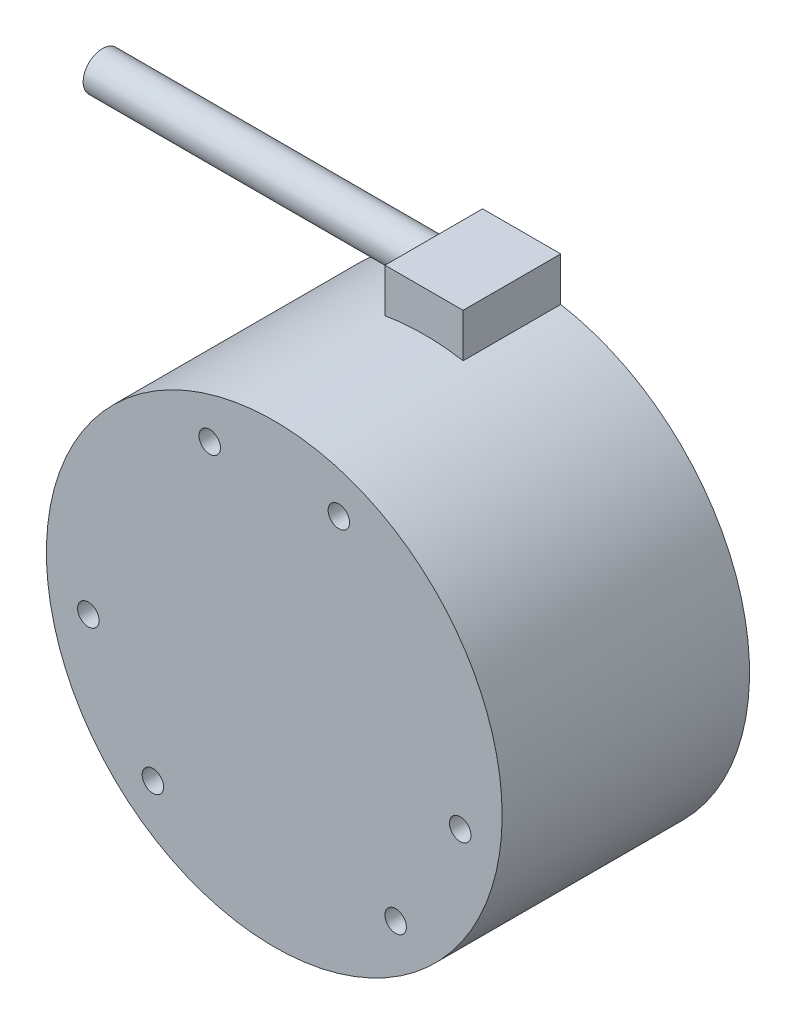
SolidWorks part; units mm, degrees
ref_plane "前视基准面" through (0, 0, 0) normal (0, 0, 1) x (1, 0, 0)
ref_plane "上视基准面" through (0, 0, 0) normal (0, 1, 0) x (1, 0, 0)
ref_plane "右视基准面" through (0, 0, 0) normal (1, 0, 0) x (0, 0, -1)
sketch "草图1" plane through (0, 0, 0) normal (0, 0, 1) x (1, 0, 0)
  circle A0 centre (0, 0) radius 35
  dimension "D1" = 70
extrude "凸台-拉伸1" add sketch "草图1" along normal blind 38
ref_plane "基准面4" through (0, 41.2, 0) normal (0, 1, 0) x (1, 0, 0)
sketch "草图2" plane through (0, 41.2, 0) normal (0, 1, 0) x (1, 0, 0)
  line L0 (35, 0) -> (-35, 0) construction
  line L1 (-6, 0) -> (6, 0)
  line L2 (-6, 0) -> (-6, -15)
  line L3 (-6, -15) -> (6, -15)
  line L4 (6, 0) -> (6, -15)
  dimension "D1" = 12
  dimension "D2" = 6
  dimension "D3" = 15
extrude "凸台-拉伸2" add sketch "草图2" against normal blind 11
sketch "草图3" plane through (6, 0, 0) normal (1, 0, 0) x (0, 0, -1)
  circle A0 centre (-7.4059, 37.7609) radius 2.95
  dimension "D1" = 5.9
extrude "凸台-拉伸3" add sketch "草图3" against normal blind 63
sketch "草图4" plane through (0, 0, 38) normal (0, 0, 1) x (1, 0, 0)
  line L0 (0, 0) -> (0, 49.7988) construction
  line L1 (0, 0) -> (-16.7034, 45.8921) construction
  line L2 (0, 0) -> (14.0808, 38.6867) construction
  circle A0 centre (0, 0) radius 29 construction
  point P5 (-9.9186, 27.2511)
  point P7 (9.9186, 27.2511)
  point P8 (28.5594, -5.0358)
  point P11 (18.6408, -22.2153)
  point P12 (-18.6408, -22.2153)
  point P13 (-28.5594, -5.0358)
  point P14 (0, 0)
  dimension "D1" = 58
  dimension "D2" = 20
  dimension "D3" = 20
  dimension "D4" = 3
hole_wizard "M4 螺纹孔的螺纹孔钻头1" positions "3D草图1" profile "草图5" hole size "M4" standard "GB"
sketch3d "3D草图1"
  point P0 (-9.9186, 27.2511, 38)
  point P3 (9.9186, 27.2511, 38)
  point P6 (28.5594, -5.0358, 38)
  point P9 (18.6408, -22.2153, 38)
  point P12 (-18.6408, -22.2153, 38)
  point P15 (-28.5594, -5.0358, 38)
sketch "草图5" plane through (-9.9186, 27.2511, 38) normal (1, 0, 0) x (0, -1, 0)
  line L0 (0, 0) -> (0, 5.9914)
  line L1 (0, 5.9914) -> (1.65, 5)
  line L2 (1.65, 5) -> (1.65, 0)
  line L5 (1.65, 0) -> (0, 0)
  line L10 (0, 5.9914) -> (-1.65, 5) construction
  line L11 (0, -6.35) -> (0, 107.95) construction
  dimension "孔直径" = 3.3
  dimension "孔深度" = 5
  dimension "导头角度" = 118
